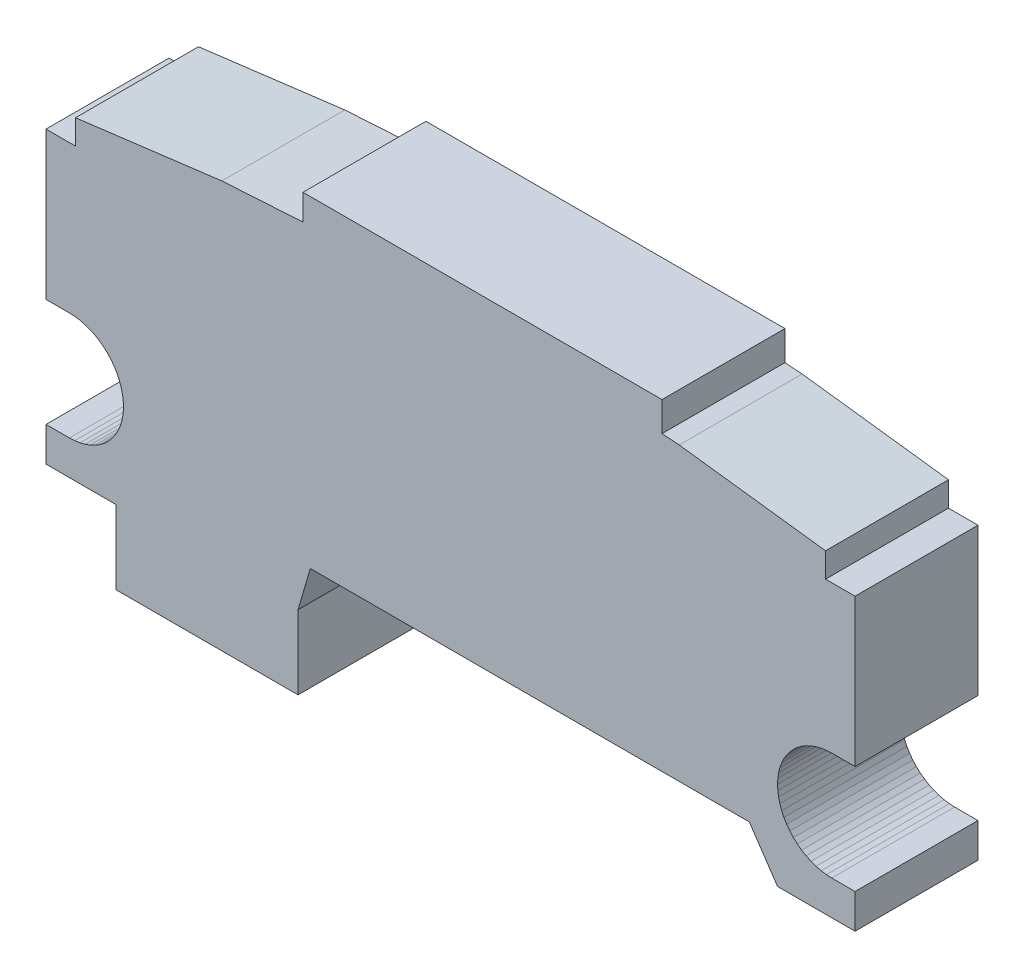
SolidWorks part; units mm, degrees
ref_plane "前视基准面" through (0, 0, 0) normal (0, 0, 1) x (1, 0, 0)
ref_plane "上视基准面" through (0, 0, 0) normal (0, 1, 0) x (1, 0, 0)
ref_plane "右视基准面" through (0, 0, 0) normal (1, 0, 0) x (0, 0, -1)
sketch "草图1" plane through (0, 0, 0) normal (0, 0, 1) x (1, 0, 0)
  line L0 (-13.6, -10.7) -> (-13.6, -7.7)
  line L1 (-13.6, -7.7) -> (-16.45, -7.7)
  line L2 (-16.45, -7.7) -> (-16.45, -6.3)
  line L3 (-16.45, -6.3) -> (-15.5, -6.3)
  line L4 (-15.5, -6.3) -> (-15.2844, -6.2894)
  line L5 (-15.2844, -6.2894) -> (-15.0708, -6.2577)
  line L6 (-15.0708, -6.2577) -> (-14.8614, -6.2053)
  line L7 (-14.8614, -6.2053) -> (-14.6581, -6.1325)
  line L8 (-14.6581, -6.1325) -> (-14.4629, -6.0402)
  line L9 (-14.4629, -6.0402) -> (-14.2778, -5.9292)
  line L10 (-14.2778, -5.9292) -> (-14.1043, -5.8006)
  line L11 (-14.1043, -5.8006) -> (-13.9444, -5.6556)
  line L12 (-13.9444, -5.6556) -> (-13.7994, -5.4957)
  line L13 (-13.7994, -5.4957) -> (-13.6708, -5.3223)
  line L14 (-13.6708, -5.3223) -> (-13.5598, -5.1371)
  line L15 (-13.5598, -5.1371) -> (-13.4675, -4.9419)
  line L16 (-13.4675, -4.9419) -> (-13.3947, -4.7386)
  line L17 (-13.3947, -4.7386) -> (-13.3423, -4.5292)
  line L18 (-13.3423, -4.5292) -> (-13.3106, -4.3157)
  line L19 (-13.3106, -4.3157) -> (-13.3, -4.1)
  line L20 (-13.3, -4.1) -> (-13.3106, -3.8844)
  line L21 (-13.3106, -3.8844) -> (-13.3423, -3.6708)
  line L22 (-13.3423, -3.6708) -> (-13.3947, -3.4614)
  line L23 (-13.3947, -3.4614) -> (-13.4675, -3.2581)
  line L24 (-13.4675, -3.2581) -> (-13.5598, -3.0629)
  line L25 (-13.5598, -3.0629) -> (-13.6708, -2.8777)
  line L26 (-13.6708, -2.8777) -> (-13.7994, -2.7043)
  line L27 (-13.7994, -2.7043) -> (-13.9444, -2.5444)
  line L28 (-13.9444, -2.5444) -> (-14.1043, -2.3994)
  line L29 (-14.1043, -2.3994) -> (-14.2778, -2.2708)
  line L30 (-14.2778, -2.2708) -> (-14.4629, -2.1598)
  line L31 (-14.4629, -2.1598) -> (-14.6581, -2.0675)
  line L32 (-14.6581, -2.0675) -> (-14.8614, -1.9947)
  line L33 (-14.8614, -1.9947) -> (-15.0708, -1.9423)
  line L34 (-15.0708, -1.9423) -> (-15.2844, -1.9106)
  line L35 (-15.2844, -1.9106) -> (-15.5, -1.9)
  line L36 (-15.5, -1.9) -> (-16.45, -1.9)
  line L37 (-16.45, -1.9) -> (-16.45, 4.1)
  line L38 (-16.45, 4.1) -> (-15.25, 4.1)
  line L39 (-15.25, 4.1) -> (-15.25, 5.1)
  line L40 (-15.25, 5.1) -> (-9.3, 5.85)
  line L41 (-9.3, 5.85) -> (-6, 6.05)
  line L42 (-6, 6.05) -> (-6, 7.1)
  line L43 (-6, 7.1) -> (8.6, 7.1)
  line L44 (8.6, 7.1) -> (8.6, 5.9)
  line L45 (8.6, 5.9) -> (9.3, 5.85)
  line L46 (9.3, 5.85) -> (15.25, 5.1)
  line L47 (15.25, 5.1) -> (15.25, 4.1)
  line L48 (15.25, 4.1) -> (16.45, 4.1)
  line L49 (16.45, 4.1) -> (16.45, -1.9)
  line L50 (16.45, -1.9) -> (15.5, -1.9)
  line L51 (15.5, -1.9) -> (15.2844, -1.9106)
  line L52 (15.2844, -1.9106) -> (15.0708, -1.9423)
  line L53 (15.0708, -1.9423) -> (14.8614, -1.9947)
  line L54 (14.8614, -1.9947) -> (14.6581, -2.0675)
  line L55 (14.6581, -2.0675) -> (14.4629, -2.1598)
  line L56 (14.4629, -2.1598) -> (14.2778, -2.2708)
  line L57 (14.2778, -2.2708) -> (14.1043, -2.3994)
  line L58 (14.1043, -2.3994) -> (13.9444, -2.5444)
  line L59 (13.9444, -2.5444) -> (13.7994, -2.7043)
  line L60 (13.7994, -2.7043) -> (13.6708, -2.8777)
  line L61 (13.6708, -2.8777) -> (13.5598, -3.0629)
  line L62 (13.5598, -3.0629) -> (13.4675, -3.2581)
  line L63 (13.4675, -3.2581) -> (13.3947, -3.4614)
  line L64 (13.3947, -3.4614) -> (13.3423, -3.6708)
  line L65 (13.3423, -3.6708) -> (13.3106, -3.8844)
  line L66 (13.3106, -3.8844) -> (13.3, -4.1)
  line L67 (13.3, -4.1) -> (13.3106, -4.3157)
  line L68 (13.3106, -4.3157) -> (13.3423, -4.5292)
  line L69 (13.3423, -4.5292) -> (13.3947, -4.7386)
  line L70 (13.3947, -4.7386) -> (13.4675, -4.9419)
  line L71 (13.4675, -4.9419) -> (13.5598, -5.1371)
  line L72 (13.5598, -5.1371) -> (13.6708, -5.3223)
  line L73 (13.6708, -5.3223) -> (13.7994, -5.4957)
  line L74 (13.7994, -5.4957) -> (13.9444, -5.6556)
  line L75 (13.9444, -5.6556) -> (14.1043, -5.8006)
  line L76 (14.1043, -5.8006) -> (14.2778, -5.9292)
  line L77 (14.2778, -5.9292) -> (14.4629, -6.0402)
  line L78 (14.4629, -6.0402) -> (14.6581, -6.1325)
  line L79 (14.6581, -6.1325) -> (14.8614, -6.2053)
  line L80 (14.8614, -6.2053) -> (15.0708, -6.2577)
  line L81 (15.0708, -6.2577) -> (15.2844, -6.2894)
  line L82 (15.2844, -6.2894) -> (15.5, -6.3)
  line L83 (15.5, -6.3) -> (16.45, -6.3)
  line L84 (16.45, -6.3) -> (16.45, -7.7)
  line L85 (16.45, -7.7) -> (13.3, -7.7)
  line L86 (13.3, -7.7) -> (12.15, -6)
  line L87 (12.15, -6) -> (-5.7, -6)
  line L88 (-5.7, -6) -> (-6.2, -7.7)
  line L89 (-6.2, -7.7) -> (-6.2, -10.7)
  line L90 (-6.2, -10.7) -> (-13.6, -10.7)
extrude "Component_Outline" add sketch "草图1" along normal blind 5 separate body
sketch3d "3D草图1"
  line L0 (0, 0, 0) -> (1, 0, 0)
  line L1 (0, 0, 0) -> (0, 1, 0)
  line L2 (0, 0, 0) -> (0, 0, 1)
  point P0 (0, 0, 0)
